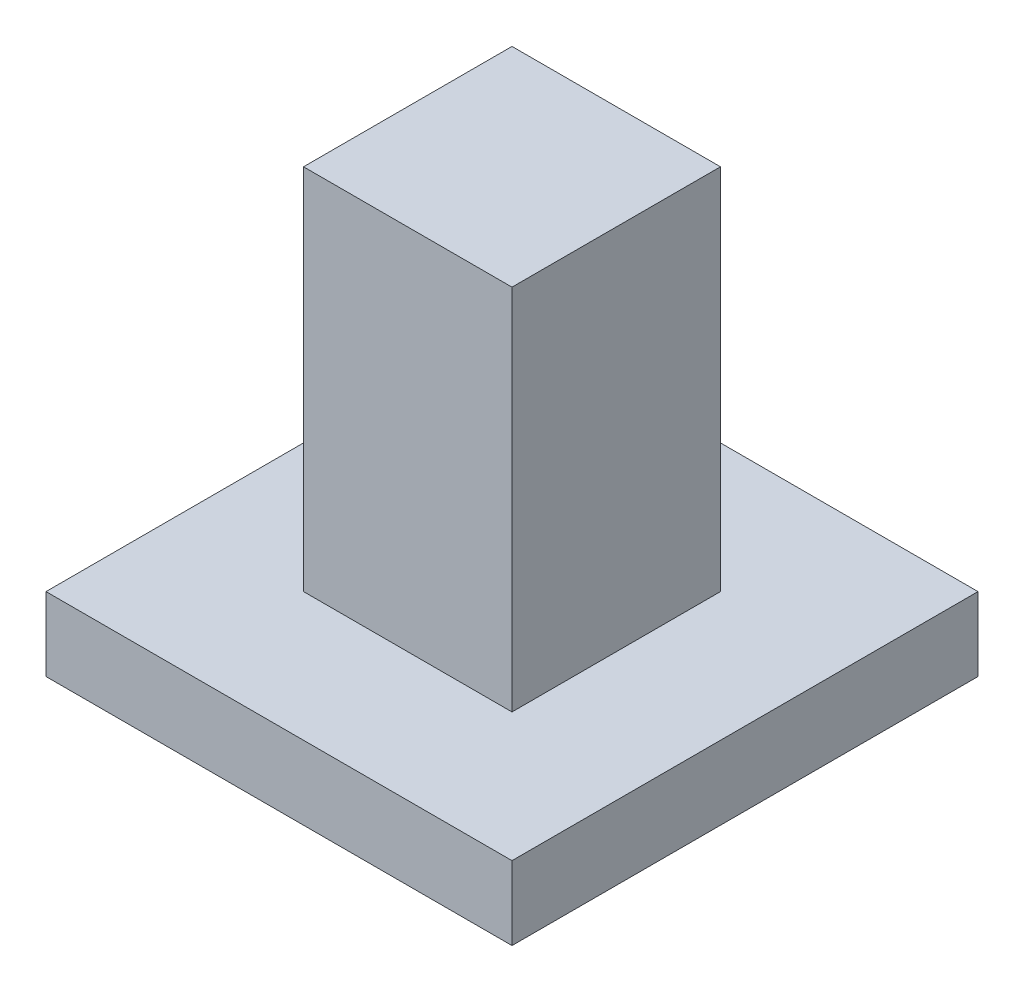
SolidWorks part; units mm, degrees
ref_plane "前视基准面" through (0, 0, 0) normal (0, 0, 1) x (1, 0, 0)
ref_plane "上视基准面" through (0, 0, 0) normal (0, 1, 0) x (1, 0, 0)
ref_plane "右视基准面" through (0, 0, 0) normal (1, 0, 0) x (0, 0, -1)
sketch "草图1" plane through (0, 0, 0) normal (0, 1, 0) x (1, 0, 0)
  line L1 (0, 0) -> (-7.6, 0)
  line L2 (0, 0) -> (0, 7.6)
  line L3 (0, 7.6) -> (-7.6, 7.6)
  line L4 (-7.6, 0) -> (-7.6, 7.6)
extrude "凸台-拉伸1" add sketch "草图1" along normal blind 1.2
sketch "草图2" plane through (0, 1.2, 0) normal (0, 1, 0) x (1, 0, 0)
  line L1 (-5.5, 5.5) -> (-2.1, 5.5)
  line L2 (-5.5, 5.5) -> (-5.5, 2.1)
  line L3 (-5.5, 2.1) -> (-2.1, 2.1)
  line L4 (-2.1, 5.5) -> (-2.1, 2.1)
extrude "凸台-拉伸2" add sketch "草图2" along normal blind 6
